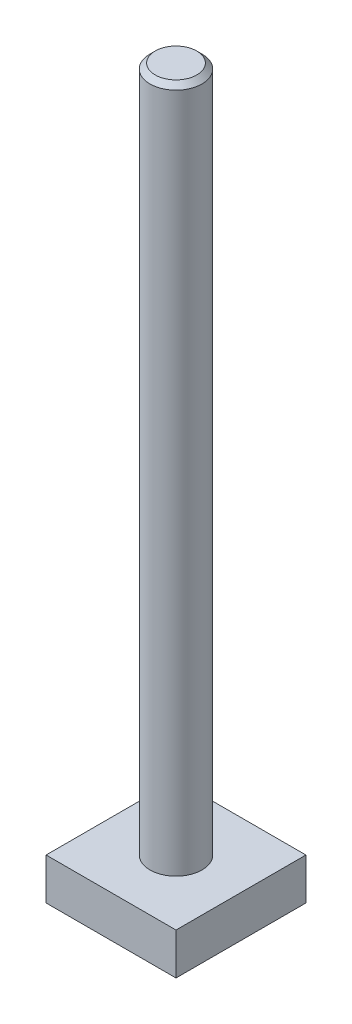
SolidWorks part; units mm, degrees
ref_plane "Front Plane" through (0, 0, 0) normal (0, 0, 1) x (1, 0, 0)
ref_plane "Top Plane" through (0, 0, 0) normal (0, 1, 0) x (1, 0, 0)
ref_plane "Right Plane" through (0, 0, 0) normal (1, 0, 0) x (0, 0, -1)
sketch "Sketch1" plane through (0, 0, 0) normal (0, 1, 0) x (1, 0, 0)
  line L1 (-12.5, 12.5) -> (12.5, 12.5)
  line L2 (-12.5, 12.5) -> (-12.5, -12.5)
  line L3 (-12.5, -12.5) -> (12.5, -12.5)
  line L4 (12.5, 12.5) -> (12.5, -12.5)
  line L5 (-12.5, 12.5) -> (12.5, -12.5) construction
  line L6 (-12.5, -12.5) -> (12.5, 12.5) construction
  point P0 (0, 0)
  dimension "D1" = 25
  dimension "D2" = 25
extrude "Boss-Extrude1" add sketch "Sketch1" along normal blind 8
sketch "Sketch2" plane through (0, 8, 0) normal (0, 1, 0) x (1, 0, 0)
  circle A0 centre (0, 0) radius 5
  dimension "D1" = 10
extrude "Boss-Extrude2" add sketch "Sketch2" along normal blind 132
chamfer "Chamfer1" distance 1 angle 45 1 edges at (0, 140, 5)
cosmetic thread "Cosmetic Thread1" parameters "D1"=38, "D2"=8.891
